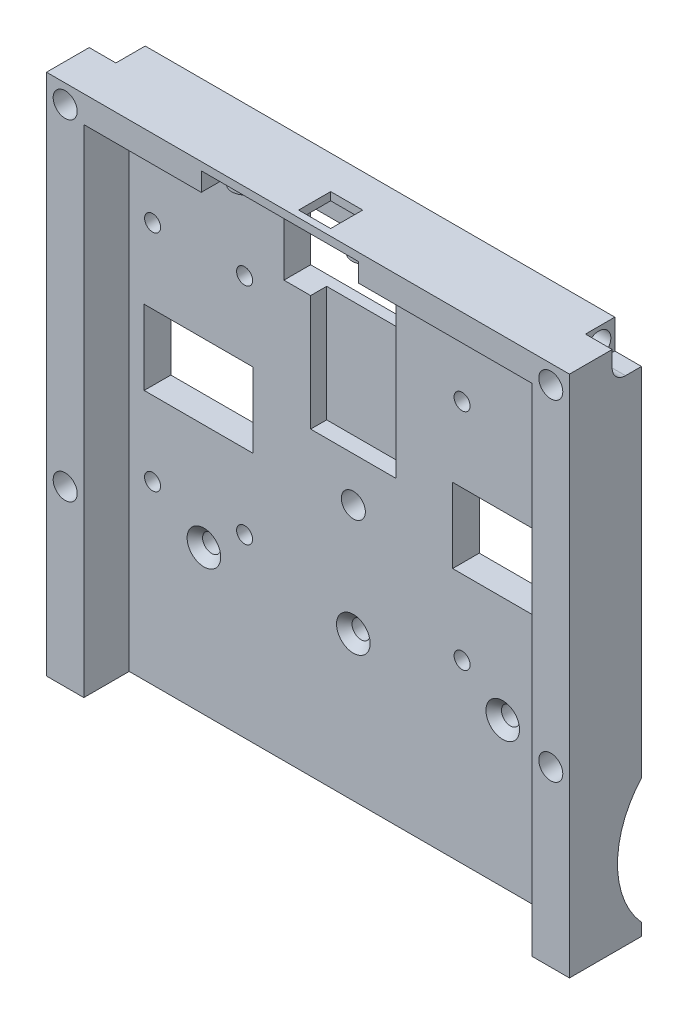
SolidWorks part; units mm, degrees
ref_plane "Front Plane" through (0, 0, 0) normal (0, 0, 1) x (1, 0, 0)
ref_plane "Top Plane" through (0, 0, 0) normal (0, 1, 0) x (1, 0, 0)
ref_plane "Right Plane" through (0, 0, 0) normal (1, 0, 0) x (0, 0, -1)
sketch "Sketch1" plane through (0, 0, 0) normal (0, 0, 1) x (1, 0, 0)
  line L1 (49, -40) -> (-49, -40)
  line L2 (49, -40) -> (49, 40)
  line L3 (49, 40) -> (-49, 40)
  line L4 (-49, -40) -> (-49, 40)
  line L5 (49, -40) -> (-49, 40) construction
  line L6 (49, 40) -> (-49, -40) construction
  point P0 (0, 0)
extrude "Boss-Extrude1" add sketch "Sketch1" along normal blind 5 contours L2 L1 L4 L3
sketch "Sketch2" plane through (0, 0, 5) normal (0, 0, 1) x (1, 0, 0)
  line L0 (49, -40) -> (-49, -40) construction
  line L1 (-49, 40) -> (-42, 40)
  line L2 (-49, 40) -> (-49, -40)
  line L3 (-49, -40) -> (-42, -40)
  line L4 (-42, 40) -> (-42, -40)
extrude "Boss-Extrude2" add sketch "Sketch2" along normal blind 8.5
sketch "Sketch3" plane through (0, 0, 5) normal (0, 0, 1) x (1, 0, 0)
  line L0 (49, -40) -> (49, 40) construction
  line L1 (49, 40) -> (42, 40)
  line L2 (49, 40) -> (49, -40)
  line L3 (49, -40) -> (42, -40)
  line L4 (42, 40) -> (42, -40)
  line L5 (49, 40) -> (-42, 40) construction
  line L6 (49, -40) -> (-42, -40) construction
extrude "Boss-Extrude3" add sketch "Sketch3" along normal blind 8.5
sketch "Sketch8" plane through (0, 40, 0) normal (0, 1, 0) x (1, 0, 0)
  line L1 (-42, -5) -> (42, -5)
  line L2 (-42, -5) -> (-42, -13.5)
  line L3 (-42, -13.5) -> (42, -13.5)
  line L4 (42, -5) -> (42, -13.5)
extrude "Boss-Extrude5" add sketch "Sketch8" against normal blind 5
sketch "Sketch13" plane through (0, 0, 5) normal (0, 0, 1) x (1, 0, 0)
  line L2 (42, -40) -> (-42, -40) construction
  line L4 (0, -40) -> (0, -10) construction
  circle A0 centre (0, -10) radius 2.25
extrude "Cut-Extrude7" cut sketch "Sketch13" against normal blind 3.25
sketch "Sketch14" plane through (0, 0, 5) normal (0, 0, 1) x (1, 0, 0)
  line L0 (0, -7.75) -> (0, 6.3272)
  line L1 (-8, 14.3272) -> (8, 14.3272)
  line L2 (-8, 14.3272) -> (-8, -1.6728)
  line L3 (8, 14.3272) -> (8, -1.6728)
  line L4 (-8, -1.6728) -> (8, -1.6728)
  line L5 (-8, 14.3272) -> (8, -1.6728) construction
  line L6 (8, 14.3272) -> (-8, -1.6728) construction
  circle A0 centre (0, -10) radius 2.25 construction
  circle A1 centre (0, -10) radius 2.25 construction
  dimension "D1" = 16
  dimension "D2" = 16
sketch "Sketch15" plane through (0, 0, 5) normal (0, 0, 1) x (1, 0, 0)
  line L0 (42, 35) -> (29, 35) construction
  line L1 (-29, 35) -> (-29, 17) construction
  line L2 (42, 35) -> (-42, 35) construction
  line L3 (-29, 17) -> (-37.62, 17) construction
  line L4 (-37.62, 17) -> (-20.38, 17) construction
  line L5 (-20.38, 17) -> (-29, 17) construction
  line L6 (-29, 17) -> (-29, -25) construction
  line L7 (-29, -25) -> (-37.62, -25) construction
  line L8 (-42, 35) -> (-29, 35) construction
  line L9 (-37.62, -25) -> (-20.38, -25) construction
  line L10 (29, 35) -> (29, 17) construction
  line L11 (29, 17) -> (20.38, 17) construction
  line L12 (20.38, 17) -> (37.62, 17) construction
  line L13 (37.62, 17) -> (29, 17) construction
  line L14 (29, 17) -> (29, -25) construction
  line L15 (29, -25) -> (20.38, -25) construction
  line L16 (20.38, -25) -> (37.62, -25) construction
  line L17 (-29, -40) -> (-29, -25) construction
  line L18 (42, -40) -> (-42, -40) construction
  line L20 (29, -25) -> (29, -40) construction
  circle A2 centre (-37.62, 17) radius 1.5
  circle A3 centre (-20.38, 17) radius 1.5
  circle A4 centre (-37.62, -25) radius 1.5
  circle A5 centre (-20.38, -25) radius 1.5
  circle A6 centre (20.38, -25) radius 1.5
  circle A7 centre (37.62, -25) radius 1.5
  circle A8 centre (37.62, 17) radius 1.5
  circle A9 centre (20.38, 17) radius 1.5
extrude "Cut-Extrude9" cut sketch "Sketch15" against normal blind 3.25
extrude "Cut-Extrude13" cut sketch "Sketch14" against normal blind 3
sketch "Sketch18" plane through (0, 0, 5) normal (0, 0, 1) x (1, 0, 0)
  line L0 (0, 35) -> (0, 26) construction
  line L1 (-42, 35) -> (42, 35) construction
  line L2 (0, 35) -> (0, 29) construction
  line L3 (-8, 32) -> (8, 32)
  line L4 (-8, 32) -> (-8, 20)
  line L5 (-8, 20) -> (8, 20)
  line L6 (8, 32) -> (8, 20)
  line L7 (-8, 32) -> (8, 20) construction
  line L8 (-8, 20) -> (8, 32) construction
extrude "Cut-Extrude14" cut sketch "Sketch18" against normal through all
sketch "Sketch19" plane through (0, 0, 5) normal (0, 0, 1) x (1, 0, 0)
  line L1 (-8, 14.3272) -> (8, 14.3272)
  line L2 (-8, 14.3272) -> (-8, 20)
  line L3 (-8, 20) -> (8, 20)
  line L4 (8, 14.3272) -> (8, 20)
extrude "Cut-Extrude15" cut sketch "Sketch19" against normal blind 3
sketch "Sketch20" plane through (0, 0, 0) normal (0, 0, -1) x (-1, 0, 0)
  line L0 (0, -40) -> (0, 10) construction
  line L1 (-49, -40) -> (49, -40) construction
  line L2 (0, 10) -> (0, 21.5) construction
  line L3 (0, 21.5) -> (0, -15) construction
  line L4 (0, 21.5) -> (18.25, 21.5) construction
  line L5 (0, 21.5) -> (-18.25, 21.5) construction
  line L6 (0, -15) -> (18.25, -15) construction
  line L7 (18.25, -15) -> (-18.25, -15) construction
  line L8 (0, 10) -> (0, 21.5) construction
  line L9 (0, 10) -> (0, -15) construction
  line L10 (0, -40) -> (0, -15) construction
  line L11 (0, -15) -> (0, 21.5) construction
  line L12 (0, -40) -> (0, -15) construction
  line L13 (0, 21.5) -> (0, 17.5) construction
  line L14 (18.25, 21.5) -> (18.25, -15) construction
  line L15 (18.25, -15) -> (-18.25, -15) construction
  line L16 (-18.25, -15) -> (-18.25, 21.5) construction
  line L17 (-18.25, 21.5) -> (18.25, 21.5) construction
  line L18 (0, -40) -> (0, -13.75) construction
  circle A0 centre (18.25, 21.5) radius 2.25
  circle A1 centre (-18.25, 21.5) radius 2.25
  circle A2 centre (18.25, -15) radius 2.25
  circle A3 centre (-18.25, -15) radius 2.25
extrude "Cut-Extrude20" cut sketch "Sketch20" against normal blind 3.25
sketch "Sketch26" plane through (0, -40, 0) normal (0, -1, 0) x (-1, 0, 0)
  line L0 (49, -13.5) -> (42, -13.5)
  line L1 (42, -13.5) -> (42, -5)
  line L2 (42, -5) -> (-42, -5)
  line L3 (-42, -5) -> (-42, -13.5)
  line L4 (-42, -13.5) -> (-49, -13.5)
  line L5 (-49, -13.5) -> (-49, 0)
  line L6 (-49, 0) -> (49, 0)
  line L7 (49, 0) -> (49, -13.5)
extrude "Boss-Extrude7" add sketch "Sketch26" along normal blind 10
sketch "Sketch42" plane through (0, 0, 13.5) normal (0, 0, 1) x (1, 0, 0)
  line L0 (-49, 40) -> (-49, 36.5) construction
  line L1 (-49, 40) -> (-49, -50) construction
  line L2 (-49, 36.5) -> (-45.5, 36.5) construction
  line L3 (-45.5, 36.5) -> (45.5, 36.5) construction
  line L4 (-45.5, 36.5) -> (-45.5, -11.5) construction
  line L5 (45.5, 36.5) -> (45.5, -11.5) construction
  circle A0 centre (-45.5, 36.5) radius 2.25
  circle A1 centre (45.5, 36.5) radius 2.25
sketch "Sketch47" plane through (0, -50, 0) normal (0, -1, 0) x (-1, 0, 0)
  line L0 (49, -13.5) -> (42, -13.5)
  line L1 (42, -13.5) -> (42, -5)
  line L2 (42, -5) -> (-42, -5)
  line L3 (-42, -5) -> (-42, -13.5)
  line L4 (-42, -13.5) -> (-49, -13.5)
  line L5 (-49, -13.5) -> (-49, 0)
  line L6 (-49, 0) -> (49, 0)
  line L7 (49, 0) -> (49, -13.5)
extrude "Boss-Extrude9" add sketch "Sketch47" along normal blind 8
sketch "Sketch48" plane through (0, 0, 5) normal (0, 0, 1) x (1, 0, 0)
  line L0 (0, -58) -> (0, -30.88) construction
  line L1 (42, -58) -> (-42, -58) construction
  line L2 (0, -30.88) -> (28, -30.88) construction
  line L3 (0, -30.88) -> (-28, -30.88) construction
hole_wizard "CSK for M3 Flat Head Machine Screw1" positions "Sketch49" profile "Sketch50" countersink size "M3" standard "ANSI Metric" end condition through all
sketch "Sketch49" plane through (0, 0, 5) normal (0, 0, 1) x (1, 0, 0)
  point P0 (28, -30.88)
  point P3 (0, -30.88)
  point P6 (-28, -30.88)
sketch "Sketch50" plane through (28, -30.88, 5) normal (1, 0, 0) x (0, -1, 0)
  line L0 (0, 0) -> (0, 5)
  line L1 (0, 5) -> (1.7, 5)
  line L2 (1.7, 5) -> (1.7, 1.45)
  line L3 (1.7, 1.45) -> (3.15, 0)
  line L5 (3.15, 0) -> (0, 0)
  line L6 (-1.7, 1.45) -> (-3.15, 0) construction
  line L11 (0, -6.35) -> (0, 107.95) construction
  dimension "Thru Hole Dia." = 3.4
  dimension "Thru Hole Depth" = 5
  dimension "Near C'Sink Dia." = 6.3
  dimension "Near C'Sink Angle" = 90
sketch "Sketch51" plane through (-49, 0, 0) normal (-1, 0, 0) x (0, 0, 1)
  line L0 (0, -58) -> (0, -44) construction
  line L1 (0, -58) -> (0, 40) construction
  line L2 (0, -44) -> (-13, -44) construction
  circle A0 centre (-13, -44) radius 17.5
extrude "Cut-Extrude23" cut sketch "Sketch51" against normal blind 8
sketch "Sketch52" plane through (49, 0, 0) normal (1, 0, 0) x (0, 0, -1)
  line L0 (0, -58) -> (0, -44) construction
  line L1 (0, -58) -> (0, 40) construction
  line L2 (0, -44) -> (13, -44) construction
  circle A0 centre (13, -44) radius 17.5
extrude "Cut-Extrude24" cut sketch "Sketch52" against normal blind 8
extrude "Cut-Extrude25" cut sketch "Sketch42" against normal blind 4.25
sketch "Sketch53" plane through (0, 0, 13.5) normal (0, 0, 1) x (1, 0, 0)
  line L0 (-45.5, 36.5) -> (-45.5, -25.5) construction
  line L1 (-45.5, -25.5) -> (45.5, -25.5) construction
  circle A0 centre (-45.5, -25.5) radius 2.25
  circle A1 centre (45.5, -25.5) radius 2.25
extrude "Cut-Extrude26" cut sketch "Sketch53" against normal blind 8.25
sketch "Sketch54" plane through (-49, 0, 0) normal (-1, 0, 0) x (0, 0, 1)
  line L0 (0, 40) -> (3, 40) construction
  line L1 (13.5, 40) -> (0, 40) construction
  line L2 (3, 40) -> (3, 37) construction
  circle A0 centre (3, 37) radius 2.25
extrude "Cut-Extrude27" cut sketch "Sketch54" against normal blind 13.25
sketch "Sketch55" plane through (-49, 0, 0) normal (-1, 0, 0) x (0, 0, 1)
  line L0 (5.5, 37) -> (5.5, 40)
  line L5 (13.5, 40) -> (0, 40) construction
  line L8 (3, 37) -> (3, 34.5) construction
  line L9 (5.5, 40) -> (0, 40)
  line L10 (0, 40) -> (0, 34.5)
  line L11 (0, -32.2846) -> (0, 40) construction
  line L12 (0, 34.5) -> (3, 34.5)
  arc A1 (3, 34.5) -> (5.5, 37) centre (3, 37) ccw
extrude "Cut-Extrude28" cut sketch "Sketch55" against normal blind 5
sketch "Sketch56" plane through (49, 0, 0) normal (1, 0, 0) x (0, 0, -1)
  line L0 (0, 40) -> (-3, 40) construction
  line L1 (-13.5, 40) -> (0, 40) construction
  line L2 (-3, 40) -> (-3, 37) construction
  circle A0 centre (-3, 37) radius 2.25
extrude "Cut-Extrude29" cut sketch "Sketch56" against normal blind 13.25
sketch "Sketch57" plane through (49, 0, 0) normal (1, 0, 0) x (0, 0, -1)
  line L0 (-5.5, 37) -> (-5.5, 40)
  line L2 (-13.5, 40) -> (-5.5, 40) construction
  line L4 (-5.5, 40) -> (0, 40)
  line L6 (0, 40) -> (0, 34.5)
  line L7 (-3, 37) -> (-3, 34.5) construction
  line L8 (0, -32.2846) -> (0, 34.5) construction
  line L9 (0, 34.5) -> (-3, 34.5)
  arc A2 (-3, 34.5) -> (-5.5, 37) centre (-3, 37) cw
extrude "Cut-Extrude30" cut sketch "Sketch57" against normal blind 5
sketch "Sketch65" plane through (0, 0, 5) normal (0, 0, 1) x (1, 0, 0)
  line L0 (-42, 35) -> (-29, 35) construction
  line L1 (-42, 35) -> (42, 35) construction
  line L2 (-29, 35) -> (-29, -4) construction
  line L3 (42, 35) -> (28.8, 35) construction
  line L4 (28.8, 35) -> (28.8, -4) construction
  line L6 (-39.2, 3) -> (-18.8, 3)
  line L7 (-39.2, 3) -> (-39.2, -11)
  line L8 (-39.2, -11) -> (-18.8, -11)
  line L9 (-18.8, 3) -> (-18.8, -11)
  line L10 (-39.2, 3) -> (-18.8, -11) construction
  line L11 (-39.2, -11) -> (-18.8, 3) construction
  line L12 (18.6, 3) -> (39, 3)
  line L13 (18.6, 3) -> (18.6, -11)
  line L14 (18.6, -11) -> (39, -11)
  line L15 (39, 3) -> (39, -11)
  line L16 (18.6, 3) -> (39, -11) construction
  line L17 (18.6, -11) -> (39, 3) construction
extrude "Cut-Extrude31" cut sketch "Sketch65" against normal through all
sketch "Sketch69" plane through (0, 35, 0) normal (0, -1, 0) x (1, 0, 0)
  line L0 (0, 13.5) -> (0, 9.25) construction
  line L4 (3, 12.25) -> (-3, 12.25)
  line L5 (3, 12.25) -> (3, 6.25)
  line L6 (3, 6.25) -> (-3, 6.25)
  line L7 (-3, 12.25) -> (-3, 6.25)
extrude "Cut-Extrude33" cut sketch "Sketch69" against normal blind 13.5
sketch "Sketch75" plane through (0, 0, 13.5) normal (0, 0, 1) x (1, 0, 0)
  line L0 (0, 40) -> (0, 38.5) construction
  line L1 (0, 38.5) -> (9.3, 38.5) construction
  line L2 (9.3, 38.5) -> (-19.2, 38.5) construction
  line L5 (-19.2, 31.5) -> (9.3, 31.5)
  line L7 (-19.2, 31.5) -> (-19.2, 38.5)
  line L8 (-19.2, 38.5) -> (9.3, 38.5)
  line L9 (9.3, 38.5) -> (9.3, 31.5)
extrude "Cut-Extrude39" cut sketch "Sketch75" against normal blind 11
sketch "Sketch77" plane through (0, 38.5, 0) normal (0, -1, 0) x (1, 0, 0)
  line L0 (-19.2, 2.5) -> (-19.2, 9.05) construction
  line L1 (-19.2, 9.05) -> (-16.2, 9.05) construction
  line L2 (9.3, 2.5) -> (9.3, 9.05) construction
  line L3 (9.3, 9.05) -> (6.3, 9.05) construction
  circle A0 centre (6.3, 9.05) radius 2.5
  circle A1 centre (-16.2, 9.05) radius 2.5
extrude "Boss-Extrude11" add sketch "Sketch77" along normal blind 2.5
sketch "Sketch79" plane through (0, 36, 0) normal (0, -1, 0) x (1, 0, 0)
  line L0 (3.8, 9.05) -> (6.3, 9.05) construction
  line L1 (-18.7, 9.05) -> (-16.2, 9.05) construction
  circle A0 centre (6.3, 9.05) radius 1.5
  circle A1 centre (-16.2, 9.05) radius 1.5
extrude "Cut-Extrude41" cut sketch "Sketch79" against normal blind 3.2
sketch "Sketch80" plane through (0, 0, 5) normal (0, 0, 1) x (1, 0, 0)
  line L1 (-8, 32) -> (-13, 32)
  line L2 (-8, 32) -> (-8, 20)
  line L3 (-8, 20) -> (-13, 20)
  line L4 (-13, 32) -> (-13, 20)
extrude "Cut-Extrude42" cut sketch "Sketch80" against normal through all
sketch "Sketch82" plane through (0, 0, 13.5) normal (0, 0, 1) x (1, 0, 0)
  line L0 (0, 40) -> (9.5, 40) construction
  line L1 (9.5, 40) -> (9.5, 38.5) construction
  line L2 (0, 40) -> (-20, 40) construction
  line L3 (-20, 40) -> (-20, 38.5) construction
  line L5 (-20, 38.5) -> (-19.2, 38.5)
  line L6 (-20, 38.5) -> (-20, 31.5)
  line L7 (-20, 31.5) -> (-19.2, 31.5)
  line L8 (-19.2, 38.5) -> (-19.2, 31.5)
  line L9 (9.5, 38.5) -> (9.3, 38.5)
  line L10 (9.5, 38.5) -> (9.5, 31.5)
  line L11 (9.5, 31.5) -> (9.3, 31.5)
  line L12 (9.3, 38.5) -> (9.3, 31.5)
extrude "Cut-Extrude43" cut sketch "Sketch82" against normal blind 11
